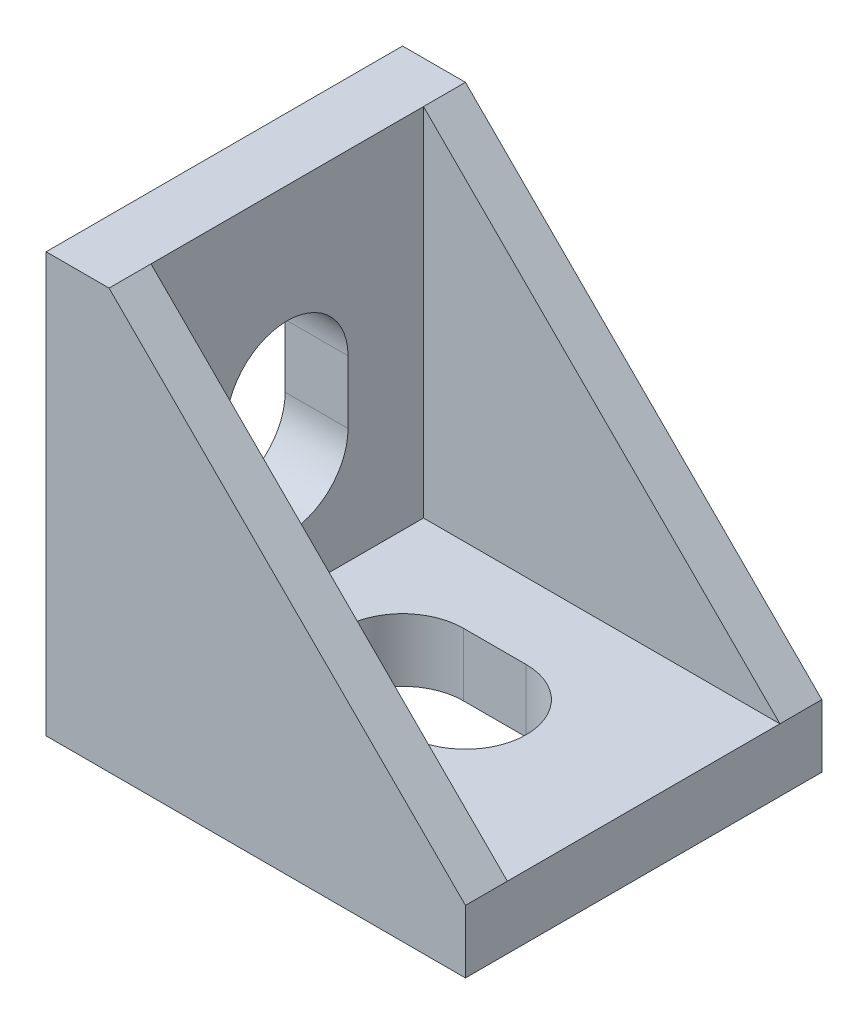
SolidWorks part; units mm, degrees
material "6061-T6 (SS)"
ref_plane "Front Plane" through (0, 0, 0) normal (0, 0, 1) x (1, 0, 0)
ref_plane "Top Plane" through (0, 0, 0) normal (0, 1, 0) x (1, 0, 0)
ref_plane "Right Plane" through (0, 0, 0) normal (1, 0, 0) x (0, 0, -1)
sketch "Sketch1" plane through (0, 0, 0) normal (0, 0, 1) x (1, 0, 0)
  line L0 (0, 0) -> (0, 20)
  line L1 (0, 20) -> (3, 20)
  line L2 (3, 20) -> (20, 3)
  line L3 (20, 3) -> (20, 0)
  line L4 (20, 0) -> (0, 0)
  dimension "D1" = 20
  dimension "D2" = 3
  dimension "D3" = 3
  dimension "D4" = 20
extrude "Boss-Extrude1" add sketch "Sketch1" along normal mid plane 17
sketch "Sketch2" plane through (0, 0, 8.5) normal (0, 0, 1) x (1, 0, 0)
  line L0 (3, 20) -> (3, 3)
  line L2 (20, 3) -> (3, 3)
  line L4 (3, 20) -> (20, 3)
extrude "Cut-Extrude1" cut sketch "Sketch2" against normal blind 13 from offset 2 offset against normal yes
sketch "Sketch3" plane through (3, 0, 0) normal (1, 0, 0) x (0, 0, -1)
  line L0 (0, 11.5) -> (0, 8.5) construction
  line L1 (2.9, 11.5) -> (2.9, 8.5)
  line L2 (-2.9, 11.5) -> (-2.9, 8.5)
  line L3 (6.5, 20) -> (-6.5, 20) construction
  arc A0 (2.9, 11.5) -> (-2.9, 11.5) centre (0, 11.5) ccw
  arc A1 (-2.9, 8.5) -> (2.9, 8.5) centre (0, 8.5) ccw
  point P3 (0, 10)
  dimension "D3" = 2.9
  dimension "D1" = 8.5
  dimension "D2" = 3
extrude "Cut-Extrude2" cut sketch "Sketch3" against normal through all
sketch "Sketch4" plane through (0, 3, 0) normal (0, 1, 0) x (1, 0, 0)
  line L0 (11.5, 0) -> (8.5, 0) construction
  line L1 (11.5, -2.9) -> (8.5, -2.9)
  line L2 (11.5, 2.9) -> (8.5, 2.9)
  line L3 (20, 6.5) -> (20, -6.5) construction
  arc A0 (11.5, -2.9) -> (11.5, 2.9) centre (11.5, 0) ccw
  arc A1 (8.5, 2.9) -> (8.5, -2.9) centre (8.5, 0) ccw
  point P3 (10, 0)
  dimension "D1" = 2.9
  dimension "D2" = 8.5
  dimension "D3" = 3
extrude "Cut-Extrude3" cut sketch "Sketch4" against normal through all
sketch "Sketch5" plane through (0, 0, 0) normal (-1, 0, 0) x (0, 0, 1)
  line L0 (8.5, 20) -> (-8.5, 20) construction
  line L1 (-2, 18.5) -> (2, 18.5)
  line L2 (-2, 18.5) -> (-2, 16.65)
  line L3 (-2, 16.65) -> (2, 16.65)
  line L4 (2, 18.5) -> (2, 16.65)
  line L5 (-2, 18.5) -> (2, 16.65) construction
  line L6 (-2, 16.65) -> (2, 18.5) construction
  line L8 (-8.5, 10) -> (8.5, 10) construction
  line L9 (-8.5, 20) -> (-8.5, 0) construction
  line L10 (8.5, 20) -> (8.5, 0) construction
  line L11 (-2, 3.35) -> (2, 1.5) construction
  line L12 (-2, 1.5) -> (2, 3.35) construction
  line L13 (2, 1.5) -> (2, 3.35)
  line L14 (-2, 3.35) -> (2, 3.35)
  line L15 (-2, 1.5) -> (-2, 3.35)
  line L16 (-2, 1.5) -> (2, 1.5)
  point P0 (0, 17.575)
  point P8 (0, 20)
  point P18 (0, 2.425)
  dimension "D1" = 4
  dimension "D2" = 1.5
  dimension "D3" = 1.85
extrude "Boss-Extrude2" add sketch "Sketch5" along normal blind 1
sketch "Sketch6" plane through (0, 0, 0) normal (0, -1, 0) x (1, 0, 0)
  line L0 (0, 8.5) -> (0, -8.5) construction
  line L1 (1.5, 2) -> (3.35, 2)
  line L2 (1.5, 2) -> (1.5, -2)
  line L3 (1.5, -2) -> (3.35, -2)
  line L4 (3.35, 2) -> (3.35, -2)
  line L5 (1.5, 2) -> (3.35, -2) construction
  line L6 (1.5, -2) -> (3.35, 2) construction
  line L7 (10, 8.5) -> (10, -8.5) construction
  line L8 (0, 8.5) -> (20, 8.5) construction
  line L9 (0, -8.5) -> (20, -8.5) construction
  line L10 (18.5, -2) -> (16.65, 2) construction
  line L11 (18.5, 2) -> (16.65, -2) construction
  line L12 (16.65, 2) -> (16.65, -2)
  line L13 (18.5, -2) -> (16.65, -2)
  line L14 (18.5, 2) -> (18.5, -2)
  line L15 (18.5, 2) -> (16.65, 2)
  point P0 (2.425, 0)
  point P18 (17.575, 0)
  dimension "D1" = 4
  dimension "D2" = 1.5
  dimension "D3" = 1.85
extrude "Boss-Extrude3" add sketch "Sketch6" along normal blind 1
